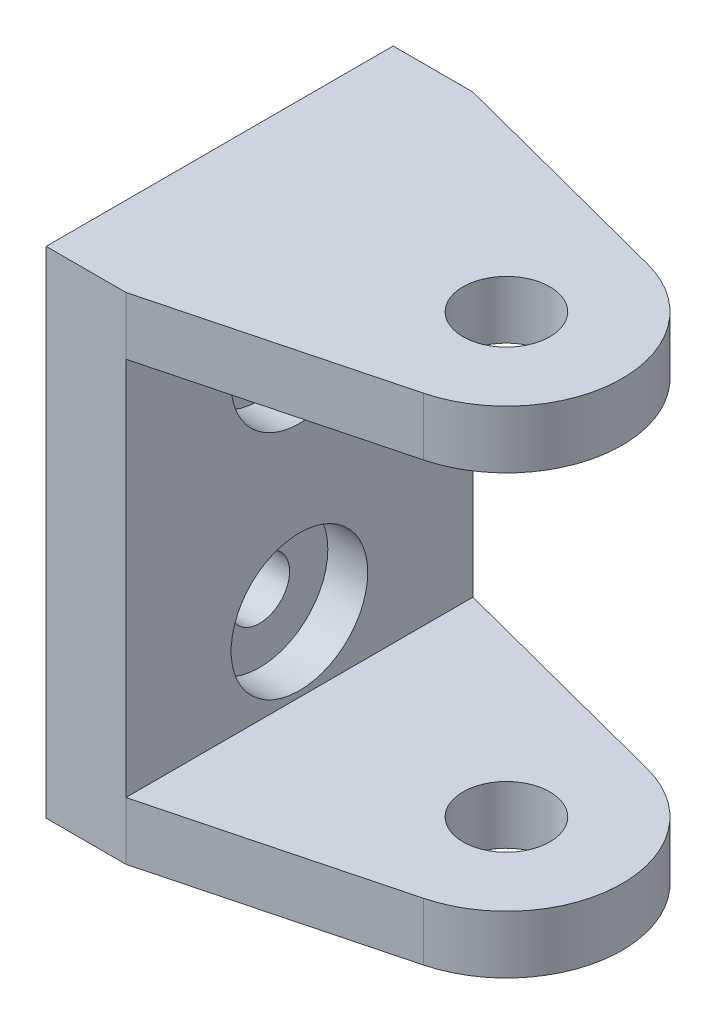
SolidWorks part; units mm, degrees
material "6061-T6 (SS)"
ref_plane "X-Y Datum" through (0, 0, 0) normal (0, 0, 1) x (1, 0, 0)
ref_plane "X-Z Datum" through (0, 0, 0) normal (0, 1, 0) x (1, 0, 0)
ref_plane "Y-Z Datum" through (0, 0, 0) normal (1, 0, 0) x (0, 0, -1)
sketch "Sketch1" plane through (0, 0, 0) normal (0, 1, 0) x (1, 0, 0)
  line L0 (15.6309, -65.821) -> (15.6309, -27.721)
  line L8 (24.3909, -65.821) -> (15.6309, -65.821)
  line L10 (15.6309, -27.721) -> (24.3909, -27.721)
  line L11 (24.3909, -27.721) -> (24.3909, -65.821)
  line L14 (4.2013, -50.8022) -> (13.7532, -50.8022) construction
  line L15 (13.2267, -42.8022) -> (6.1059, -42.8022) construction
  line L16 (4.2013, -46.771) -> (13.2267, -46.771) construction
  point P14 (0, 0)
  dimension "D1" = 38.1
  dimension "D2" = 3.9688
  dimension "D3" = 19.05
  dimension "D4" = 8.76
extrude "Boss-Extrude1" add sketch "Sketch1" along normal blind 54.3789
sketch "Sketch3" plane through (15.6309, 0, 0) normal (-1, 0, 0) x (0, 0, 1)
  line L0 (27.721, 0) -> (65.821, 0) construction
  line L1 (65.821, 54.3789) -> (65.821, 0) construction
  point P0 (46.771, 39.8894)
  point P1 (46.771, 14.4894)
  dimension "D1" = 25.4
  dimension "D2" = 14.4894
  dimension "D3" = 19.05
hole_wizard "CBORE for M6 Hex Head Bolt1" positions "Sketch4" profile "Sketch5" counterbore size "M6" standard "ANSI Metric"
sketch "Sketch4" plane through (24.3909, 0, 0) normal (1, 0, 0) x (0, 0, -1)
  point P0 (-46.771, 14.4894)
  point P3 (-46.771, 39.8894)
sketch "Sketch5" plane through (24.3909, 14.4894, 46.771) normal (0, 1, 0) x (0, 0, -1)
  line L0 (0, 0) -> (0, 16.002)
  line L1 (0, 16.002) -> (3.3, 14.0192)
  line L2 (3.3, 14.0192) -> (3.3, 4.38)
  line L3 (3.3, 4.38) -> (7.5, 4.38)
  line L4 (7.5, 4.38) -> (7.5, 0)
  line L5 (7.5, 0) -> (0, 0)
  line L10 (0, 16.002) -> (-3.3, 14.0192) construction
  line L11 (0, -6.35) -> (0, 107.95) construction
  dimension "Hole Dia." = 6.6
  dimension "Hole Depth" = 16.002
  dimension "C'Bore Dia." = 15
  dimension "C'Bore Depth" = 4.38
  dimension "Drill Angle" = 118
sketch "Sketch6" plane through (0, 54.3789, 0) normal (0, 1, 0) x (1, 0, 0)
  line L2 (24.3909, -27.721) -> (24.3909, -65.821)
  line L3 (24.3909, -65.821) -> (50.3228, -59.0602)
  line L4 (24.3909, -27.721) -> (50.3228, -34.4817)
  circle A2 centre (47.1189, -46.771) radius 4.7625
  arc A3 (50.3228, -59.0602) -> (50.3228, -34.4817) centre (47.1189, -46.771) ccw
  point P3 (47.1189, -46.771)
  dimension "D1" = 9.525
  dimension "D2" = 25.4
extrude "Boss-Extrude2" add sketch "Sketch6" against normal blind 6.35
ref_plane "Plane1" through (0, 27.1894, 0) normal (0, 1, 0) x (1, 0, 0)
mirror "Mirror1" about plane through (0, 27.1894, 0) normal (0, 1, 0) of "Boss-Extrude2"
